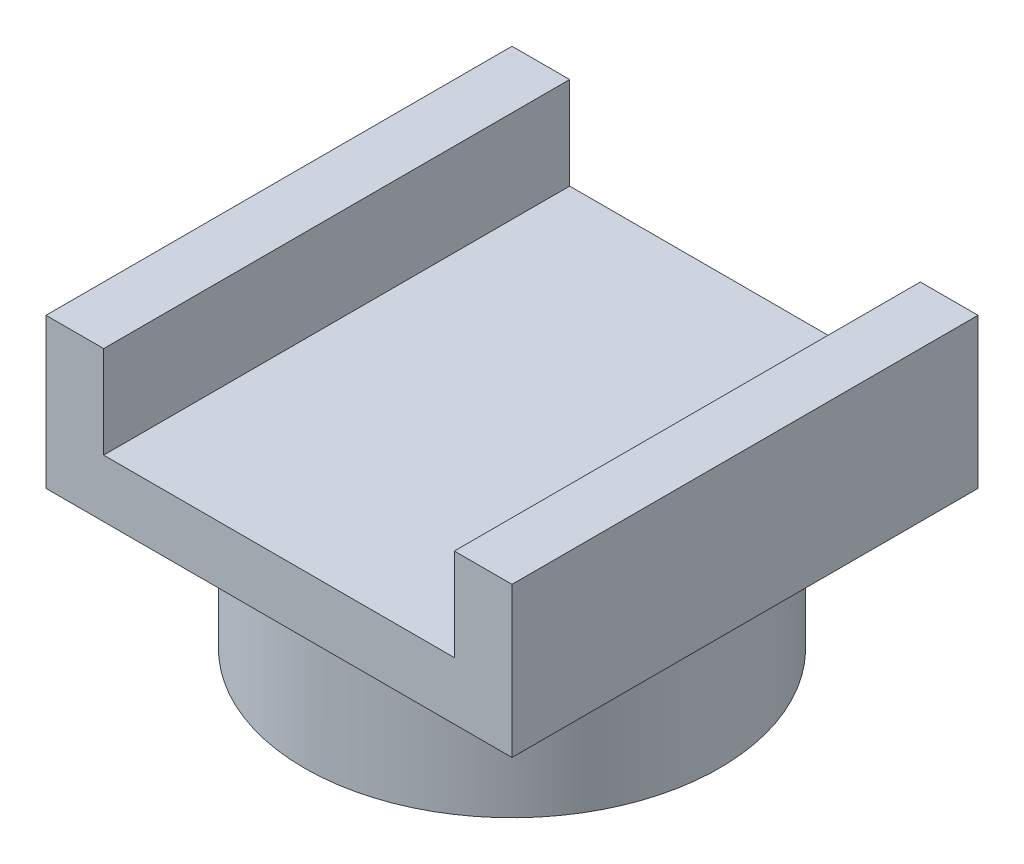
SolidWorks part; units mm, degrees
ref_plane "Front Plane" through (0, 0, 0) normal (0, 0, 1) x (1, 0, 0)
ref_plane "Top Plane" through (0, 0, 0) normal (0, 1, 0) x (1, 0, 0)
ref_plane "Right Plane" through (0, 0, 0) normal (1, 0, 0) x (0, 0, -1)
sketch "Sketch1" plane through (0, 0, 0) normal (0, 1, 0) x (1, 0, 0)
  line L0 (0, 15.5) -> (0, -15.5) construction
  line L1 (-15.5, 0) -> (15.5, 0) construction
  line L2 (-2.4674, 13.4022) -> (-4, 4) construction
  line L3 (4, -4) -> (-4, -4) construction
  line L4 (4, -4) -> (4, 4) construction
  line L5 (4, 4) -> (-4, 4) construction
  line L6 (-4, -4) -> (-4, 4) construction
  line L7 (4, -4) -> (-4, 4) construction
  line L8 (4, 4) -> (-4, -4) construction
  line L9 (-4, 4) -> (-2.4674, 13.4022)
  line L10 (4, 4) -> (2.4674, 13.4022)
  line L11 (4, -4) -> (2.4674, -13.4022)
  line L12 (-4, -4) -> (-2.4674, -13.4022)
  line L13 (-4, 4) -> (-12.5927, 2.4331) construction
  line L14 (-4, 4) -> (-12.4485, 2.4594)
  line L15 (-4, -4) -> (-12.4485, -2.4594)
  line L16 (4, -4) -> (12.4485, -2.4594)
  line L17 (4, 4) -> (12.4485, 2.4594)
  circle A0 centre (0, 0) radius 15.5 construction
  circle A1 centre (0, 0) radius 14.5 construction
  arc A2 (2.4674, 13.4022) -> (-2.4674, 13.4022) centre (0, 13) ccw
  arc A3 (2.4674, -13.4022) -> (-2.4674, -13.4022) centre (0, -13) cw
  arc A4 (-12.4485, 2.4594) -> (-12.4485, -2.4594) centre (-12, 0) ccw
  arc A5 (12.4485, 2.4594) -> (12.4485, -2.4594) centre (12, 0) cw
  circle A6 centre (0, 0) radius 12 construction
  circle A7 centre (0, 0) radius 9.5 construction
  circle A8 centre (0, 0) radius 7.5 construction
  circle A9 centre (0, 12) radius 0.5
  circle A10 centre (0, 9.5) radius 0.5
  circle A11 centre (0, 7.5) radius 0.5
  circle A12 centre (12, 0) radius 0.5
  circle A13 centre (9.5, 0) radius 0.5
  circle A14 centre (7.5, 0) radius 0.5
  circle A15 centre (0, -12) radius 0.5
  circle A16 centre (0, -9.5) radius 0.5
  circle A17 centre (0, -7.5) radius 0.5
  circle A18 centre (-12, 0) radius 0.5
  circle A19 centre (-9.5, 0) radius 0.5
  circle A20 centre (-7.5, 0) radius 0.5
  circle A21 centre (0, 0) radius 1.375
  point P59 (0, 0)
  dimension "D1" = 31
  dimension "D2" = 1
  dimension "D3" = 5
  dimension "D4" = 5
  dimension "D5" = 8
  dimension "D6" = 8
  dimension "D7" = 15
  dimension "D9" = 24
  dimension "D11" = 1
  dimension "D12" = 1
  dimension "D13" = 4
  dimension "D8" = 19
  dimension "D10" = 1
  dimension "D14" = 2.75
extrude "Boss-Extrude1" add sketch "Sketch1" along normal blind 2
sketch "Sketch4" plane through (0, 0, 0) normal (0, -1, 0) x (1, 0, 0)
  circle A0 centre (0, 0) radius 4.5
  circle A1 centre (0, 0) radius 2.5
  dimension "D1" = 9
  dimension "D2" = 2
extrude "Boss-Extrude3" add sketch "Sketch4" along normal blind 3
sketch "Sketch5" plane through (0, -3, 0) normal (0, -1, 0) x (1, 0, 0)
  line L0 (0, 0) -> (0, 0.6245) construction
  line L1 (0, 3) -> (-0.299, 2.4821)
  line L2 (0, 3) -> (0.299, 2.4821)
  line L3 (0.9271, 2.8532) -> (0.4826, 2.453)
  line L4 (0.9271, 2.8532) -> (1.0514, 2.2682)
  line L5 (1.7634, 2.4271) -> (1.217, 2.1838)
  line L6 (1.7634, 2.4271) -> (1.7008, 1.8323)
  line L7 (2.4271, 1.7634) -> (1.8323, 1.7008)
  line L8 (2.4271, 1.7634) -> (2.1838, 1.217)
  line L9 (2.8532, 0.9271) -> (2.2682, 1.0514)
  line L10 (2.8532, 0.9271) -> (2.453, 0.4826)
  line L11 (3, 0) -> (2.4821, 0.299)
  line L12 (3, 0) -> (2.4821, -0.299)
  line L13 (2.8532, -0.9271) -> (2.453, -0.4826)
  line L14 (2.8532, -0.9271) -> (2.2682, -1.0514)
  line L15 (2.4271, -1.7634) -> (2.1838, -1.217)
  line L16 (2.4271, -1.7634) -> (1.8323, -1.7008)
  line L17 (1.7634, -2.4271) -> (1.7008, -1.8323)
  line L18 (1.7634, -2.4271) -> (1.217, -2.1838)
  line L19 (0.9271, -2.8532) -> (1.0514, -2.2682)
  line L20 (0.9271, -2.8532) -> (0.4826, -2.453)
  line L21 (0, -3) -> (0.299, -2.4821)
  line L22 (0, -3) -> (-0.299, -2.4821)
  line L23 (-0.9271, -2.8532) -> (-0.4826, -2.453)
  line L24 (-0.9271, -2.8532) -> (-1.0514, -2.2682)
  line L25 (-1.7634, -2.4271) -> (-1.217, -2.1838)
  line L26 (-1.7634, -2.4271) -> (-1.7008, -1.8323)
  line L27 (-2.4271, -1.7634) -> (-1.8323, -1.7008)
  line L28 (-2.4271, -1.7634) -> (-2.1838, -1.217)
  line L29 (-2.8532, -0.9271) -> (-2.2682, -1.0514)
  line L30 (-2.8532, -0.9271) -> (-2.453, -0.4826)
  line L31 (-3, 0) -> (-2.4821, -0.299)
  line L32 (-3, 0) -> (-2.4821, 0.299)
  line L33 (-2.8532, 0.9271) -> (-2.453, 0.4826)
  line L34 (-2.8532, 0.9271) -> (-2.2682, 1.0514)
  line L35 (-2.4271, 1.7634) -> (-2.1838, 1.217)
  line L36 (-2.4271, 1.7634) -> (-1.8323, 1.7008)
  line L37 (-1.7634, 2.4271) -> (-1.7008, 1.8323)
  line L38 (-1.7634, 2.4271) -> (-1.217, 2.1838)
  line L39 (-0.9271, 2.8532) -> (-1.0514, 2.2682)
  line L40 (-0.9271, 2.8532) -> (-0.4826, 2.453)
  circle A0 centre (0, 0) radius 2.5 construction
  arc A1 (-2.1838, 1.217) -> (-2.2682, 1.0514) centre (0, 0) ccw
  arc A2 (-1.7008, 1.8323) -> (-1.8323, 1.7008) centre (0, 0) ccw
  arc A3 (-1.0514, 2.2682) -> (-1.217, 2.1838) centre (0, 0) ccw
  arc A4 (-0.299, 2.4821) -> (-0.4826, 2.453) centre (0, 0) ccw
  arc A5 (0.4826, 2.453) -> (0.299, 2.4821) centre (0, 0) ccw
  arc A6 (1.217, 2.1838) -> (1.0514, 2.2682) centre (0, 0) ccw
  arc A7 (1.8323, 1.7008) -> (1.7008, 1.8323) centre (0, 0) ccw
  arc A8 (2.2682, 1.0514) -> (2.1838, 1.217) centre (0, 0) ccw
  arc A9 (2.4821, 0.299) -> (2.453, 0.4826) centre (0, 0) ccw
  arc A10 (2.453, -0.4826) -> (2.4821, -0.299) centre (0, 0) ccw
  arc A11 (2.1838, -1.217) -> (2.2682, -1.0514) centre (0, 0) ccw
  arc A12 (1.7008, -1.8323) -> (1.8323, -1.7008) centre (0, 0) ccw
  arc A13 (1.0514, -2.2682) -> (1.217, -2.1838) centre (0, 0) ccw
  arc A14 (0.299, -2.4821) -> (0.4826, -2.453) centre (0, 0) ccw
  arc A15 (-0.4826, -2.453) -> (0, -2.5) centre (0, 0) ccw
  arc A16 (-1.217, -2.1838) -> (-1.0514, -2.2682) centre (0, 0) ccw
  arc A17 (-1.8323, -1.7008) -> (-1.7008, -1.8323) centre (0, 0) ccw
  arc A18 (-2.2682, -1.0514) -> (-2.1838, -1.217) centre (0, 0) ccw
  arc A19 (-2.4821, -0.299) -> (-2.453, -0.4826) centre (0, 0) ccw
  arc A20 (-2.453, 0.4826) -> (-2.4821, 0.299) centre (0, 0) ccw
  point P68 (0, 0)
  circle M5 centre (0, 0) radius 2.5
  dimension "D1" = 30
  dimension "D2" = 3
  dimension "D3" = 20
extrude "Cut-Extrude3" cut sketch "Sketch5" against normal up to surface (3 mm away) contours L36 L35 M5 | L34 L33 M5 | L32 L31 M5 | L30 L29 M5 | L28 L27 M5 | L26 L25 M5 | L24 L23 M5 | L0 L21 M5 | L22 L0 M5 | L20 L19 M5 | L18 L17 M5 | L16 L15 M5 | L14 L13 M5 | L12 L11 M5 | L10 L9 M5 | L8 L7 M5 | L6 L5 M5 | L4 L3 M5 | L0 L2 M5 | L0 L1 M5 | L40 L39 M5 | L38 L37 M5
sketch "Sketch6" plane through (0, 0, 0) normal (0, -1, 0) x (-1, 0, 0)
  line L1 (17.0148, 16.8983) -> (-17.0148, 16.8983)
  line L2 (17.0148, 16.8983) -> (17.0148, -16.8983)
  line L3 (17.0148, -16.8983) -> (-17.0148, -16.8983)
  line L4 (-17.0148, 16.8983) -> (-17.0148, -16.8983)
  line L5 (17.0148, 16.8983) -> (-17.0148, -16.8983) construction
  line L6 (17.0148, -16.8983) -> (-17.0148, 16.8983) construction
  point P0 (0, 0)
extrude "Cut-Extrude4" cut sketch "Sketch6" against normal through all
sketch "Sketch7" plane through (0, 0, 0) normal (0, 1, 0) x (1, 0, 0)
  line L1 (-5.05, -5.05) -> (5.05, -5.05)
  line L2 (-5.05, -5.05) -> (-5.05, 5.05)
  line L3 (-5.05, 5.05) -> (5.05, 5.05)
  line L4 (5.05, -5.05) -> (5.05, 5.05)
  line L5 (-5.05, -5.05) -> (5.05, 5.05) construction
  line L6 (-5.05, 5.05) -> (5.05, -5.05) construction
  point P0 (0, 0)
  dimension "D1" = 10.1
  dimension "D2" = 10.1
extrude "Boss-Extrude4" add sketch "Sketch7" along normal blind 1.25
sketch "Sketch8" plane through (0, 1.25, 0) normal (0, 1, 0) x (1, 0, 0)
  line L0 (-5.05, -5.05) -> (5.05, -5.05) construction
  line L1 (-5.05, 5.05) -> (-3.8, 5.05)
  line L2 (-5.05, 5.05) -> (-5.05, -5.05)
  line L3 (-5.05, -5.05) -> (-3.8, -5.05)
  line L4 (-3.8, 5.05) -> (-3.8, -5.05)
  line L6 (5.05, 5.05) -> (3.8, 5.05)
  line L7 (5.05, 5.05) -> (5.05, -5.05)
  line L8 (5.05, -5.05) -> (3.8, -5.05)
  line L9 (3.8, 5.05) -> (3.8, -5.05)
  dimension "D1" = 1.25
  dimension "D2" = 1.25
extrude "Boss-Extrude5" add sketch "Sketch8" along normal blind 2 contours L2 L1 L4 L3 | L7 L6 L9 L8
